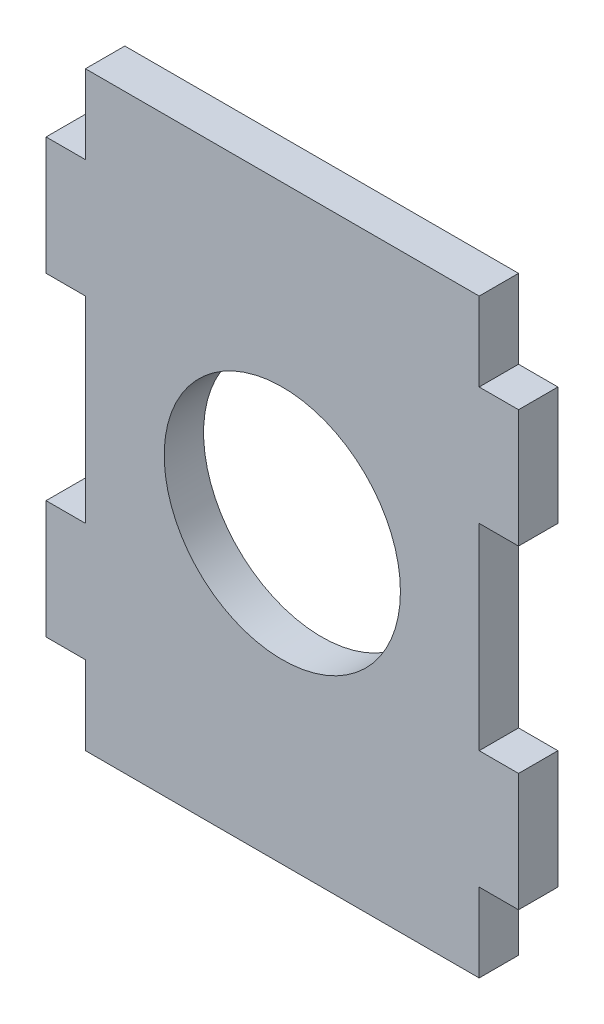
SolidWorks part; units mm, degrees
ref_plane "Front Plane" through (0, 0, 0) normal (0, 0, 1) x (1, 0, 0)
ref_plane "Top Plane" through (0, 0, 0) normal (0, 1, 0) x (1, 0, 0)
ref_plane "Right Plane" through (0, 0, 0) normal (1, 0, 0) x (0, 0, -1)
sketch "Sketch1" plane through (0, 0, 0) normal (0, 0, 1) x (1, 0, 0)
  line L1 (15.875, -23.8125) -> (-15.875, -23.8125)
  line L2 (15.875, -23.8125) -> (15.875, 23.8125)
  line L3 (15.875, 23.8125) -> (-15.875, 23.8125)
  line L4 (-15.875, -23.8125) -> (-15.875, 23.8125)
  line L5 (15.875, -23.8125) -> (-15.875, 23.8125) construction
  line L6 (15.875, 23.8125) -> (-15.875, -23.8125) construction
  line L7 (15.875, 17.4625) -> (19.05, 17.4625)
  line L8 (15.875, 17.4625) -> (15.875, 7.9375)
  line L9 (15.875, 7.9375) -> (19.05, 7.9375)
  line L10 (19.05, 17.4625) -> (19.05, 7.9375)
  line L11 (15.875, -17.4625) -> (19.05, -17.4625)
  line L12 (15.875, -17.4625) -> (15.875, -7.9375)
  line L13 (15.875, -7.9375) -> (19.05, -7.9375)
  line L14 (19.05, -17.4625) -> (19.05, -7.9375)
  line L15 (-15.875, 7.9375) -> (-19.05, 7.9375)
  line L16 (-15.875, 7.9375) -> (-15.875, 17.4625)
  line L17 (-15.875, 17.4625) -> (-19.05, 17.4625)
  line L18 (-19.05, 7.9375) -> (-19.05, 17.4625)
  line L19 (-15.875, -17.4625) -> (-19.05, -17.4625)
  line L20 (-15.875, -17.4625) -> (-15.875, -7.9375)
  line L21 (-15.875, -7.9375) -> (-19.05, -7.9375)
  line L22 (-19.05, -17.4625) -> (-19.05, -7.9375)
  circle A0 centre (0, 0) radius 9.525
  point P0 (0, 0)
  dimension "D15" = 19.05
  dimension "D1" = 31.75
  dimension "D2" = 47.625
  dimension "D3" = 3.175
  dimension "D4" = 9.525
  dimension "D5" = 9.525
  dimension "D6" = 9.525
  dimension "D7" = 9.525
  dimension "D8" = 3.175
  dimension "D9" = 3.175
  dimension "D10" = 3.175
  dimension "D11" = 6.35
  dimension "D12" = 6.35
  dimension "D13" = 6.35
  dimension "D14" = 6.35
extrude "Boss-Extrude1" add sketch "Sketch1" along normal blind 3.175 contours L18 L15 L4 L17 | L4 L1 L2 L3 A0 | L22 L19 L4 L21 | L10 L7 L2 L9 | L11 L14 L13 L2
